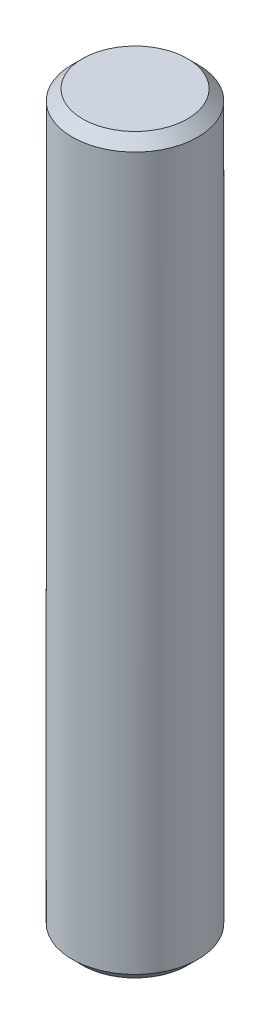
SolidWorks part; units mm, degrees
ref_plane "Front Plane" through (0, 0, 0) normal (0, 0, 1) x (1, 0, 0)
ref_plane "Top Plane" through (0, 0, 0) normal (0, 1, 0) x (1, 0, 0)
ref_plane "Right Plane" through (0, 0, 0) normal (1, 0, 0) x (0, 0, -1)
sketch "Sketch1" plane through (0, 0, 0) normal (1, 0, 0) x (0, 0, -1)
  line L1 (0, 0) -> (6, 0)
  line L2 (0, 0) -> (0, 70)
  line L3 (0, 70) -> (6, 70)
  line L4 (6, 0) -> (6, 70)
  dimension "D1" = 70
  dimension "D2" = 6
revolve "Revolve1" add sketch "Sketch1" angle 360 about L2
cosmetic thread "Cosmetic Thread1" parameters "D1"=40, "D2"=10.072
cosmetic thread "Cosmetic Thread2" parameters "D1"=14, "D2"=10.072
chamfer "Chamfer1" distance 1 angle 45 2 edges at (0, 0, -6) (0, 70, -6)
